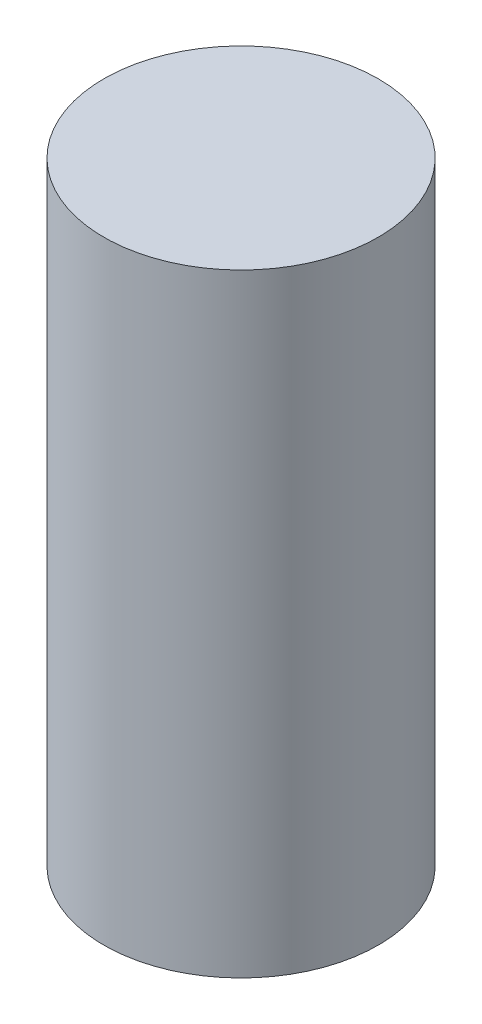
SolidWorks part; units mm, degrees
ref_plane "Front Plane" through (0, 0, 0) normal (0, 0, 1) x (1, 0, 0)
ref_plane "Top Plane" through (0, 0, 0) normal (0, 1, 0) x (1, 0, 0)
ref_plane "Right Plane" through (0, 0, 0) normal (1, 0, 0) x (0, 0, -1)
sketch "Sketch1" plane through (0, 0, 0) normal (0, 1, 0) x (1, 0, 0)
  line L0 (0, 0) -> (-131.3975, -49.2086) construction
  circle A0 centre (0, -45.445) radius 1.925
extrude "Boss-Extrude1" add sketch "Sketch1" along normal blind 8.6
